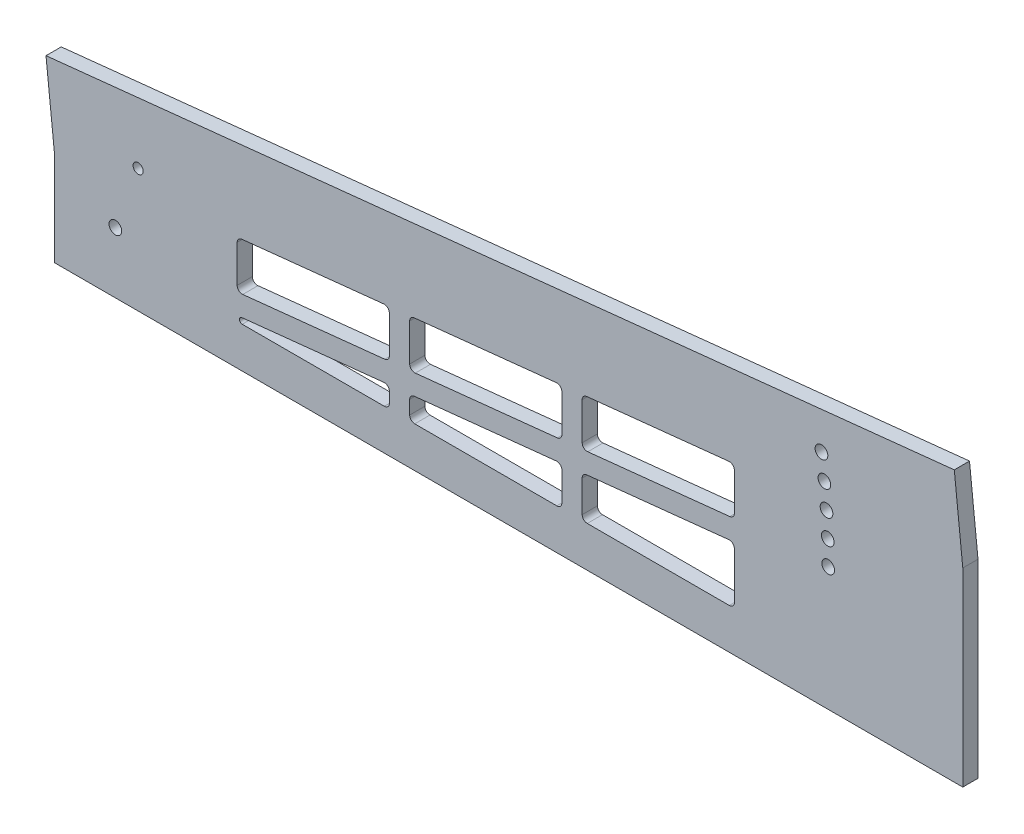
SolidWorks part; units mm, degrees
material "Pine"
ref_plane "Front Plane" through (0, 0, 0) normal (0, 0, 1) x (1, 0, 0)
ref_plane "Top Plane" through (0, 0, 0) normal (0, 1, 0) x (1, 0, 0)
ref_plane "Right Plane" through (0, 0, 0) normal (1, 0, 0) x (0, 0, -1)
sketch "Sketch1" plane through (0, 0, 0) normal (0, 0, 1) x (1, 0, 0)
  line L0 (-10.6201, 219.0942) -> (1126.1184, 338.5703)
  line L1 (1126.1184, 338.5703) -> (1136.7385, 237.5268)
  line L2 (1136.7385, 237.5268) -> (0, 118.0508) construction
  line L3 (0, 118.0508) -> (-10.6201, 219.0942)
  line L4 (0, 118.0508) -> (0, 0)
  line L5 (0, 0) -> (1136.7385, 0)
  line L6 (1136.7385, 0) -> (1136.7385, 237.5268)
  line L7 (0, 118.0508) -> (1136.7385, 118.0508) construction
  dimension "D1" = 1143
  dimension "D2" = 101.6
  dimension "D3" = 118.0508
  dimension "D4" = 6
extrude "Boss-Extrude1" add sketch "Sketch1" along normal blind 19.05
sketch "Sketch3" [suppressed] plane through (0, 0, 19.05) normal (0, 0, 1) x (1, 0, 0)
  line L0 (93.1354, -242.5766) -> (408.4688, -242.5766) construction
  line B0 (221.5466, -65.8912) -> (52.3501, -63.5412)
  arc B1 (731.486, 25.7569) -> (660.9874, 53.9563) centre (734.4449, 135.377) cw
  spline B2 degree 3 poles (52.3501, -63.5412) (59.4, -57.2747) (64.9444, -48.7137) (73.4997, -44.7416) (87.4583, -38.2608) (102.9844, -35.6165) (118.1487, -32.9919) (143.8059, -28.5512) (169.9355, -27.3805) (195.6971, -23.5921) (196.7931, -23.4309) (197.0131, -21.6398) (198.0471, -21.2421) (217.473, -13.7706) (237.3699, -7.5641) (256.7958, -0.0926) (257.8298, 0.3051) (258.1296, 1.8164) (259.1458, 2.2574) (299.7181, 19.8642) (340.9438, 35.9565) (381.3433, 53.9563) (420.0735, 71.2124) (456.7375, 93.258) (496.4909, 108.0052) (506.0382, 111.547) (516.883, 108.7307) (527.0402, 108.0052) (528.1452, 107.9263) (528.3844, 106.1195) (529.3902, 105.6552) (548.8157, 96.6896) (568.7134, 88.7714) (588.1389, 79.8058) (589.1448, 79.3416) (589.5464, 78.038) (590.4889, 77.4558) (616.2054, 61.5721) (640.7876, 43.5367) (668.0373, 30.4568) (680.3702, 24.537) (694.3438, 22.0676) (707.9865, 21.057) (715.9529, 20.4669) (723.6528, 24.1903) (731.486, 25.7569) knots 0 0 0 0 1 1 1 2 2 2 3 3 3 4 4 4 5 5 5 6 6 6 7 7 7 8 8 8 9 9 9 10 10 10 11 11 11 12 12 12 13 13 13 14 14 14 15 15 15 15
  spline B3 degree 3 poles (660.9874, 53.9563) (664.904, 57.0896) (668.3424, 60.939) (672.7372, 63.3561) (684.0984, 69.6048) (695.5775, 76.0455) (707.9865, 79.8058) (721.6663, 83.9512) (736.1859, 84.5057) (750.2856, 86.8556) knots 0 0 0 0 1 1 1 2 2 2 3 3 3 3
  spline B4 degree 3 poles (750.2856, 86.8556) (751.0689, 86.0723) (751.5704, 84.81) (752.6355, 84.5057) (762.6842, 81.6346) (773.1362, 80.3269) (783.1849, 77.4558) (784.25, 77.1515) (784.5831, 75.6728) (785.5348, 75.1059) (821.429, 53.7222) (856.7292, 31.2479) (893.6326, 11.6572) (920.2584, -2.4775) (948.3154, -13.7409) (975.8809, -25.942) (996.1025, -34.8926) (1017.2003, -41.9018) (1036.9796, -51.7915) (1042.4516, -54.5275) (1045.5354, -60.9541) (1051.0793, -63.5412) (1057.6236, -66.5952) (1065.3776, -65.9574) (1072.2289, -68.2411) (1079.5478, -70.6808) (1088.3258, -71.811) (1093.3784, -77.6409) (1099.3832, -84.5695) (1099.645, -94.8739) (1102.7782, -103.4904) knots 0 0 0 0 1 1 1 2 2 2 3 3 3 4 4 4 5 5 5 6 6 6 7 7 7 8 8 8 9 9 9 10 10 10 10
sketch_block_instance "Block1-1"
sketch_block "Block1"
sketch "Sketch5" [suppressed] plane through (0, 0, 19.05) normal (0, 0, 1) x (1, 0, 0)
  line L0 (13.2751, -329.5043) -> (1112.1224, -329.5043) construction
sketch_block_instance "KSU Logo-1"
sketch_block "KSU Logo"
sketch "Sketch6" [suppressed] plane through (0, 0, 19.05) normal (0, 0, 1) x (1, 0, 0)
  line L0 (13.2751, -329.5043) -> (1112.2917, -329.5043)
  arc A0 (644.4772, -182.5663) -> (719.2506, -209.2264) centre (717.9864, -94.5838) ccw construction
  arc A1 (644.4772, -182.5663) -> (719.2506, -209.2264) centre (717.9864, -94.5838) ccw
  spline S0 degree 3 poles (-1280.3103, 1192.4596) (70.4152, -589.6915) (-25.4983, -339.7665) (34.624, -309.0232) (48.9497, -301.6978) (65.0655, -298.3182) (80.8041, -294.9736) (107.4329, -289.3148) (134.6851, -287.0536) (161.4489, -282.072) (162.5875, -281.8601) (162.7462, -279.9801) (163.8106, -279.5235) (183.8089, -270.9458) (204.3494, -263.671) (224.3477, -255.0934) (225.4121, -254.6368) (225.6653, -253.046) (226.7094, -252.5449) (268.3976, -232.5382) (310.8285, -214.0878) (352.3204, -193.6774) (392.0981, -174.1104) (429.5267, -149.6216) (470.4728, -132.635) (480.3066, -128.5554) (491.7485, -131.0668) (502.3891, -131.4212) (503.5466, -131.4597) (503.8683, -133.3379) (504.9375, -133.7829) (525.5885, -142.3779) (546.6911, -149.8598) (567.3421, -158.4547) (568.4113, -158.8998) (568.8827, -160.2457) (569.8905, -160.8165) (597.3888, -176.3891) (623.7875, -194.2548) (652.7762, -206.8372) (665.8961, -212.5318) (680.5931, -214.5566) (694.8864, -215.0703) (756.2736, -217.2767) (793.3222, 23.7242) (1074.5457, -2175.2338) knots -5.847463 -5.847463 -5.847463 -5.847463 1 1 1 2 2 2 3 3 3 4 4 4 5 5 5 6 6 6 7 7 7 8 8 8 9 9 9 10 10 10 11 11 11 12 12 12 13 13 13 14 14 14 21.354953 21.354953 21.354953 21.354953 only from (13.2751, -329.5043) to (719.2506, -209.2264) construction
  spline S1 degree 3 poles (13.2751, -329.5043) (20.3914, -322.6772) (25.8438, -313.5129) (34.624, -309.0232) (48.9497, -301.6978) (65.0655, -298.3182) (80.8041, -294.9736) (107.4329, -289.3148) (134.6851, -287.0536) (161.4489, -282.072) (162.5875, -281.8601) (162.7462, -279.9801) (163.8106, -279.5235) (183.8089, -270.9458) (204.3494, -263.671) (224.3477, -255.0934) (225.4121, -254.6368) (225.6653, -253.046) (226.7094, -252.5449) (268.3976, -232.5382) (310.8285, -214.0878) (352.3204, -193.6774) (392.0981, -174.1104) (429.5267, -149.6216) (470.4728, -132.635) (480.3066, -128.5554) (491.7485, -131.0668) (502.3891, -131.4212) (503.5466, -131.4597) (503.8683, -133.3379) (504.9375, -133.7829) (525.5885, -142.3779) (546.6911, -149.8598) (567.3421, -158.4547) (568.4113, -158.8998) (568.8827, -160.2457) (569.8905, -160.8165) (597.3888, -176.3891) (623.7875, -194.2548) (652.7762, -206.8372) (665.8961, -212.5318) (680.5931, -214.5566) (694.8864, -215.0703) (703.2328, -215.3703) (711.1292, -211.1744) (719.2506, -209.2264) knots 0 0 0 0 1 1 1 2 2 2 3 3 3 4 4 4 5 5 5 6 6 6 7 7 7 8 8 8 9 9 9 10 10 10 11 11 11 12 12 12 13 13 13 14 14 14 15 15 15 15
  spline S2 degree 3 poles (-241.4428, -1889.1202) (782.5147, -13.4023) (726.4576, -143.9324) (739.0123, -147.0086) (749.6246, -149.6088) (760.5963, -150.5598) (771.2087, -153.1601) (772.3336, -153.4357) (772.7403, -154.9673) (773.7571, -155.5218) (812.107, -176.4361) (849.8797, -198.5135) (889.2127, -217.5144) (917.5914, -231.2236) (947.3515, -241.8763) (976.6351, -253.528) (998.1172, -262.0756) (1020.4374, -268.5602) (1041.4947, -278.1065) (1047.3203, -280.7475) (1050.7974, -287.3391) (1056.6922, -289.8218) (1063.6506, -292.7524) (1071.7263, -291.7779) (1078.9748, -293.8916) (1086.7181, -296.1496) (1095.9338, -296.9816) (1101.4442, -302.8717) (1143.8023, -348.1486) (940.7534, -550.5313) (2873.3021, 614.2618) knots -10.160638 -10.160638 -10.160638 -10.160638 1 1 1 2 2 2 3 3 3 4 4 4 5 5 5 6 6 6 7 7 7 8 8 8 9 9 9 15.468178 15.468178 15.468178 15.468178 only from (736.4638, -144.6469) to (1112.2917, -329.5043) construction
  spline S3 degree 3 poles (-635.8429, 1351.8798) (668.935, -363.0189) (612.6207, -198.5602) (656.3792, -172.2791) (668.0005, -165.2994) (679.7373, -158.1144) (692.5521, -153.6928) (801.1717, -116.2149) (970.0813, -298.5423) (503.9584, 1834.3294) knots -8.734019 -8.734019 -8.734019 -8.734019 1 1 1 2 2 2 9.688637 9.688637 9.688637 9.688637 only from (644.4772, -182.5663) to (736.4638, -144.6469) construction
  spline S4 degree 3 poles (736.4638, -144.6469) (737.3133, -145.4341) (737.8874, -146.733) (739.0123, -147.0086) (749.6246, -149.6088) (760.5963, -150.5598) (771.2087, -153.1601) (772.3336, -153.4357) (772.7403, -154.9673) (773.7571, -155.5218) (812.107, -176.4361) (849.8797, -198.5135) (889.2127, -217.5144) (917.5914, -231.2236) (947.3515, -241.8763) (976.6351, -253.528) (998.1172, -262.0756) (1020.4374, -268.5602) (1041.4947, -278.1065) (1047.3203, -280.7475) (1050.7974, -287.3391) (1056.6922, -289.8218) (1063.6506, -292.7524) (1071.7263, -291.7779) (1078.9748, -293.8916) (1086.7181, -296.1496) (1095.9338, -296.9816) (1101.4442, -302.8717) (1107.9929, -309.8716) (1108.6758, -320.6267) (1112.2917, -329.5043) knots 0 0 0 0 1 1 1 2 2 2 3 3 3 4 4 4 5 5 5 6 6 6 7 7 7 8 8 8 9 9 9 10 10 10 10
  spline S5 degree 3 poles (644.4772, -182.5663) (648.4446, -179.1372) (651.8838, -174.979) (656.3792, -172.2791) (668.0005, -165.2994) (679.7373, -158.1144) (692.5521, -153.6928) (706.6794, -148.8184) (721.8266, -147.6622) (736.4638, -144.6469) knots 0 0 0 0 1 1 1 2 2 2 3 3 3 3
extrude "Cut-Extrude1" [suppressed] cut sketch "Sketch6" against normal through all
sketch "Sketch7" plane through (0, 0, 19.05) normal (0, 0, 1) x (1, 0, 0)
  line L0 (0, 118.0508) -> (1136.7385, 237.5268) construction
  line L1 (-5.31, 168.5725) -> (57.8421, 175.2101) construction
  line L2 (-10.6201, 219.0942) -> (0, 118.0508) construction
  line L3 (57.8421, 175.2101) -> (1066.841, 228.0895) construction
  line L4 (57.8421, 175.2101) -> (1055.7862, 333.2689) construction
  line L5 (57.8421, 175.2101) -> (1068.2763, 281.411) construction
  line L6 (1136.7385, 237.5268) -> (1126.1184, 338.5703) construction
  line L7 (1055.7862, 333.2689) -> (1066.841, 228.0895) construction
  line L8 (1062.9663, 331.9327) -> (1073.5864, 230.8893) construction
  line L9 (1126.1184, 338.5703) -> (-10.6201, 219.0942) construction
  arc A0 (1055.7862, 333.2689) -> (1066.841, 228.0895) centre (866.1895, 260.1708) cw
  arc A1 (1053.5644, 332.4123) -> (1064.4896, 228.4654) centre (866.1895, 260.1708) cw
  arc A2 (1058.008, 334.1255) -> (1069.1924, 227.7135) centre (866.1895, 260.1708) cw
  arc A3 (1053.5644, 332.4123) -> (1058.008, 334.1255) centre (1055.7862, 333.2689) cw
  arc A4 (1064.4896, 228.4654) -> (1069.1924, 227.7135) centre (1066.841, 228.0895) ccw
  circle A5 centre (57.8421, 175.2101) radius 2.3812
  point P9 (1068.2763, 281.411)
  point P12 (1061.3136, 280.6792)
  point P15 (1068.2763, 281.411)
  dimension "D3" = 203.2
  dimension "D5" = 4.7625
  dimension "D6" = 4.7625
  dimension "D1" = 63.5
  dimension "D2" = 3
  dimension "D4" = 63.5
extrude "Cut-Extrude2" [suppressed] cut sketch "Sketch7" against normal through all
sketch "Sketch9" plane through (0, 0, 19.05) normal (0, 0, 1) x (1, 0, 0)
  line L4 (0, 0) -> (1136.7385, 0) construction
  line L5 (1136.7385, 0) -> (1136.7385, 237.5268) construction
  arc A7 (1050.8774, 281.1663) -> (1071.4143, 85.7709) centre (131.6143, 85.7709) cw construction
  arc A8 (1050.8774, 281.1663) -> (1071.4143, 85.7709) centre (131.6143, 85.7709) cw construction
  arc A9 (1073.7956, 85.7709) -> (1053.2067, 281.6614) centre (131.6143, 85.7709) ccw
  arc A10 (1069.0331, 85.7709) -> (1048.5482, 280.6712) centre (131.6143, 85.7709) ccw
  arc A11 (1069.0331, 85.7709) -> (1073.7956, 85.7709) centre (1071.4143, 85.7709) ccw
  arc A12 (1053.2067, 281.6614) -> (1048.5482, 280.6712) centre (1050.8774, 281.1663) ccw
  point P0 (1071.4143, 85.7709)
  point P7 (1050.8774, 281.1663)
  point P12 (1066.266, 184.0067)
  point P15 (1066.266, 184.0067)
  dimension "D7" = 4.7625
  dimension "D1" = 281.1663
  dimension "D2" = 184.0067
  dimension "D3" = 85.7709
  dimension "D4" = 65.3242
  dimension "D5" = 70.4725
  dimension "D6" = 85.8611
extrude "Cut-Extrude4" [suppressed] cut sketch "Sketch9" against normal through all
sketch "Sketch8" plane through (0, 0, 19.05) normal (0, 0, 1) x (1, 0, 0)
  circle A4 centre (104.7036, 154.5955) radius 6.35
  dimension "D3" = 12.7
  dimension "D1" = 154.5955
  dimension "D2" = 104.7036
extrude "Cut-Extrude3" cut sketch "Sketch8" against normal through all
sketch "Sketch10" plane through (0, 0, 19.05) normal (0, 0, 1) x (1, 0, 0)
  circle A7 centre (963.5727, 244.8663) radius 7.9375
  circle A9 centre (966.1999, 214.8372) radius 7.9375
  circle A11 centre (967.7775, 184.7347) radius 7.9375
  circle A13 centre (968.3036, 154.5955) radius 7.9375
  circle A15 centre (959.8991, 274.7854) radius 7.9375
  dimension "D1" = 15.875
other "AlignGroup1"
other "AlignGroup2"
extrude "Cut-Extrude5" cut sketch "Sketch10" against normal through all
sketch "Sketch11" plane through (0, 0, 19.05) normal (0, 0, 1) x (1, 0, 0)
  line L0 (563.0592, 338.5703) -> (563.0592, 0) construction
  line L1 (-10.6201, 338.5703) -> (1136.7385, 338.5703) construction
  line L2 (-10.6201, 338.5703) -> (-10.6201, 0) construction
  line L3 (-10.6201, 0) -> (1136.7385, 0) construction
  line L4 (1136.7385, 338.5703) -> (1136.7385, 0) construction
  circle A2 centre (987.6885, 157.1625) radius 6.35
  dimension "D1" = 149.05
  dimension "D3" = 12.7
  dimension "D2" = 157.1625
ref_plane "Plane1" through (563.0592, 0, 0) normal (-1, 0, 0) x (0, -1, 0)
sketch "Sketch12" plane through (0, 0, 19.05) normal (0, 0, 1) x (1, 0, 0)
  line L2 (844.55, 50.8) -> (666.75, 50.8)
  line L3 (444.5, 57.15) -> (444.5, 74.1244)
  line L4 (1126.1184, 338.5703) -> (-10.6201, 219.0942) construction
  line L9 (843.8862, 206.7468) -> (666.0862, 188.0593)
  line L10 (660.4, 181.7441) -> (660.4, 135.1263)
  line L11 (635, 57.15) -> (635, 92.812)
  line L12 (627.9862, 184.0548) -> (450.1862, 165.3673)
  line L13 (0, 0) -> (1136.7385, 0) construction
  line L14 (627.9862, 184.0548) -> (666.0862, 188.0593) construction
  line L15 (628.65, 50.8) -> (666.75, 50.8) construction
  line L16 (660.4, 115.304) -> (635, 115.304) construction
  line L18 (628.65, 50.8) -> (450.85, 50.8)
  line L19 (850.9, 200.4316) -> (850.9, 153.8138)
  line L21 (647.7, 0) -> (647.7, 288.2865) construction
  line L22 (412.75, 50.8) -> (234.95, 50.8)
  line L24 (234.2862, 142.6753) -> (412.0862, 161.3628)
  line L25 (419.1, 155.0476) -> (419.1, 108.4298)
  line L26 (444.5, 105.3819) -> (419.1, 105.3819) construction
  line L27 (413.4138, 102.1146) -> (235.6138, 83.4271)
  line L28 (234.5842, 57.779) -> (412.0862, 76.4352)
  line L29 (845.2138, 147.4986) -> (667.4138, 128.8111)
  line L30 (228.6, 69.92) -> (850.9, 135.3263) construction
  line L31 (540.4138, 115.4629) -> (543.0688, 90.202) construction
  line L32 (228.6, 89.7423) -> (228.6, 136.3601)
  line L33 (419.1, 70.12) -> (419.1, 57.15)
  line L34 (444.5, 112.4343) -> (444.5, 159.0521)
  line L35 (635, 131.1218) -> (635, 177.7396)
  line L36 (660.4, 96.8164) -> (660.4, 57.15)
  line L37 (850.9, 115.504) -> (850.9, 57.15)
  line L38 (228.6, 82.6899) -> (228.6, 57.15) construction
  line L39 (419.1, 102.7123) -> (419.1, 77.1724) construction
  line L40 (666.0862, 103.1317) -> (843.8862, 121.8192)
  line L41 (444.5, 79.842) -> (444.5, 105.3819) construction
  line L42 (635, 125.4043) -> (635, 99.8644) construction
  line L43 (660.4, 128.0739) -> (660.4, 102.534) construction
  line L44 (850.9, 148.0963) -> (850.9, 122.5564) construction
  line L45 (0, 118.0508) -> (0, 0) construction
  line L46 (450.1862, 80.4397) -> (627.9862, 99.1272)
  line L47 (629.3138, 124.8066) -> (451.5138, 106.1191)
  line L48 (234.5842, 57.779) -> (228.6, 57.15) construction
  arc A0 (450.1862, 165.3673) -> (444.5, 159.0521) centre (450.85, 159.0521) ccw
  arc A1 (450.85, 50.8) -> (444.5, 57.15) centre (450.85, 57.15) cw
  arc A2 (635, 57.15) -> (628.65, 50.8) centre (628.65, 57.15) cw
  arc A3 (635, 177.7396) -> (627.9862, 184.0548) centre (628.65, 177.7396) ccw
  arc A4 (666.0862, 188.0593) -> (660.4, 181.7441) centre (666.75, 181.7441) ccw
  arc A5 (660.4, 57.15) -> (666.75, 50.8) centre (666.75, 57.15) ccw
  arc A6 (850.9, 57.15) -> (844.55, 50.8) centre (844.55, 57.15) cw
  arc A7 (843.8862, 206.7468) -> (850.9, 200.4316) centre (844.55, 200.4316) cw
  arc A8 (234.95, 50.8) -> (228.6, 57.15) centre (234.95, 57.15) cw construction
  arc A9 (412.75, 50.8) -> (419.1, 57.15) centre (412.75, 57.15) ccw
  arc A10 (412.0862, 161.3628) -> (419.1, 155.0476) centre (412.75, 155.0476) cw
  arc A11 (228.6, 136.3601) -> (234.2862, 142.6753) centre (234.95, 136.3601) cw
  arc A12 (660.4, 96.8164) -> (666.0862, 103.1317) centre (666.75, 96.8164) cw
  arc A13 (843.8862, 121.8192) -> (850.9, 115.504) centre (844.55, 115.504) cw
  arc A14 (845.2138, 147.4986) -> (850.9, 153.8138) centre (844.55, 153.8138) ccw
  arc A15 (660.4, 135.1263) -> (667.4138, 128.8111) centre (666.75, 135.1263) ccw
  arc A16 (635, 131.1218) -> (629.3138, 124.8066) centre (628.65, 131.1218) cw
  arc A17 (635, 92.812) -> (627.9862, 99.1272) centre (628.65, 92.812) ccw
  arc A18 (444.5, 74.1244) -> (450.1862, 80.4397) centre (450.85, 74.1244) cw
  arc A19 (419.1, 70.12) -> (412.0862, 76.4352) centre (412.75, 70.12) ccw
  arc A20 (444.5, 112.4343) -> (451.5138, 106.1191) centre (450.85, 112.4343) ccw
  arc A21 (419.1, 108.4298) -> (413.4138, 102.1146) centre (412.75, 108.4298) cw
  arc A22 (235.6138, 83.4271) -> (228.6, 89.7423) centre (234.95, 89.7423) cw
  arc A23 (234.5842, 57.779) -> (234.95, 50.8) centre (234.95, 54.2991) ccw
  point P32 (444.5, 50.8)
  point P45 (850.9, 50.8)
  point P78 (540.4138, 115.4629)
  dimension "D7" = 6.35
  dimension "D5" = 6.35
  dimension "D9" = 6.35
  dimension "D1" = 101.6
  dimension "D2" = 25.4
  dimension "D3" = 228.6
  dimension "D4" = 50.8
  dimension "D6" = 406.4
  dimension "D8" = 190.5
extrude "Cut-Extrude6" cut sketch "Sketch12" against normal through all
sketch "Sketch13" plane through (0, 0, 19.05) normal (0, 0, 1) x (1, 0, 0)
  line L0 (0, 0) -> (1136.7385, 0) construction
  line L1 (0, 118.0508) -> (0, 0) construction
  circle A1 centre (76.2, 76.2) radius 7.9375
  point P3 (0, 0)
  dimension "D1" = 15.875
  dimension "D2" = 76.2
  dimension "D3" = 76.2
extrude "Cut-Extrude7" cut sketch "Sketch13" against normal through all
